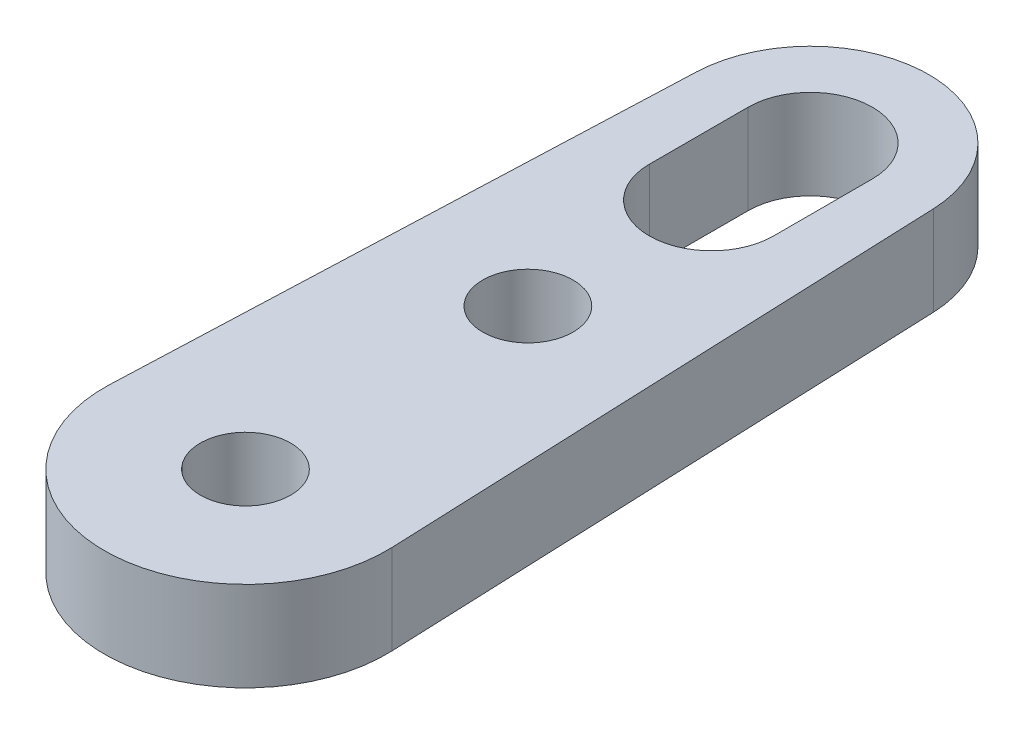
SolidWorks part; units mm, degrees
ref_plane "Front Plane" through (0, 0, 0) normal (0, 0, 1) x (1, 0, 0)
ref_plane "Top Plane" through (0, 0, 0) normal (0, 1, 0) x (1, 0, 0)
ref_plane "Right Plane" through (0, 0, 0) normal (1, 0, 0) x (0, 0, -1)
sketch "Sketch1" plane through (0, 0, 0) normal (0, 1, 0) x (1, 0, 0)
  line L0 (-4.1966, 20.168) -> (-4.996, 0.2)
  line L5 (4.1966, 20.168) -> (4.996, 0.2)
  line L6 (0, 0) -> (0, 20) construction
  arc A2 (-4.996, 0.2) -> (4.996, 0.2) centre (0, 0) ccw
  arc A3 (4.1966, 20.168) -> (-4.1966, 20.168) centre (0, 20) ccw
  dimension "D1" = 4.2
  dimension "D2" = 5
  dimension "D3" = 20
extrude "Boss-Extrude1" add sketch "Sketch1" along normal blind 3.175
sketch "Sketch2" plane through (0, 3.175, 0) normal (0, 1, 0) x (1, 0, 0)
  line L0 (0, 0) -> (0, 10) construction
  circle A0 centre (0, 0) radius 1.6
  circle A1 centre (0, 10) radius 1.6
  dimension "D1" = 3.2
  dimension "D2" = 10
extrude "Cut-Extrude1" cut sketch "Sketch2" against normal through all
sketch "Sketch3" plane through (0, 3.175, 0) normal (0, 1, 0) x (1, 0, 0)
  line L0 (0, 16.5) -> (0, 20) construction
  line L1 (-2.2, 16.5) -> (-2.2, 20)
  line L2 (2.2, 16.5) -> (2.2, 20)
  arc A0 (-2.2, 16.5) -> (2.2, 16.5) centre (0, 16.5) ccw
  arc A1 (2.2, 20) -> (-2.2, 20) centre (0, 20) ccw
  arc A2 (4.1966, 20.168) -> (-4.1966, 20.168) centre (0, 20) ccw construction
  point P2 (0, 18.25)
  dimension "D1" = 2.2
  dimension "D2" = 3.5
extrude "Cut-Extrude2" cut sketch "Sketch3" against normal through all
